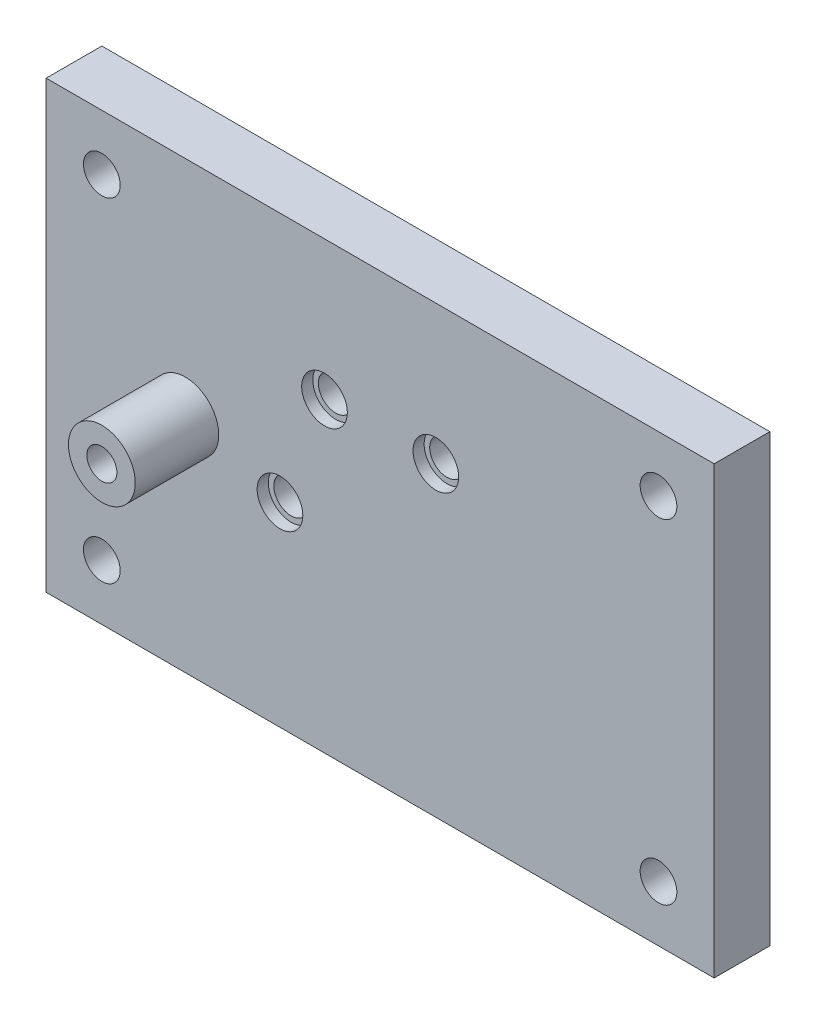
SolidWorks part; units mm, degrees
ref_plane "Front Plane" through (0, 0, 0) normal (0, 0, 1) x (1, 0, 0)
ref_plane "Top Plane" through (0, 0, 0) normal (0, 1, 0) x (1, 0, 0)
ref_plane "Right Plane" through (0, 0, 0) normal (1, 0, 0) x (0, 0, -1)
other "Configuration Table"
sketch "Sketch2" plane through (0, 0, 0) normal (0, 0, 1) x (1, 0, 0)
  line L1 (-60, -40) -> (60, -40)
  line L2 (-60, -40) -> (-60, 40)
  line L3 (-60, 40) -> (60, 40)
  line L4 (60, -40) -> (60, 40)
extrude "Base_plate" add sketch "Sketch2" along normal blind 10 from offset 0
sketch "Sketch3" plane through (0, 0, 0) normal (0, 0, 1) x (1, 0, 0)
  circle A0 centre (-35, 0) radius 6
extrude "Pivot_pedestal" add sketch "Sketch3" along normal blind 15 from offset 10
sketch "Sketch4" plane through (0, 0, 0) normal (0, 0, 1) x (1, 0, 0)
  circle A0 centre (-35, 0) radius 2.7
extrude "Pivot_clearance" cut sketch "Sketch4" along normal blind 25 from offset 0
sketch "Sketch5" plane through (0, 0, 0) normal (0, 0, 1) x (1, 0, 0)
  circle A0 centre (-10, 15) radius 3.1
extrude "Locator_clearance" cut sketch "Sketch5" along normal blind 10 from offset 0
sketch "Sketch6" plane through (0, 0, 0) normal (0, 0, 1) x (1, 0, 0)
  circle A0 centre (10, 15) radius 3.1
extrude "Cut-Extrude3" cut sketch "Sketch6" along normal blind 10 from offset 0
sketch "Sketch7" plane through (0, 0, 0) normal (0, 0, 1) x (1, 0, 0)
  circle A0 centre (-18, -5) radius 3.1
extrude "Side_locator_clearance" cut sketch "Sketch7" along normal blind 10 from offset 0
sketch "Sketch8" plane through (0, 0, 0) normal (0, 0, 1) x (1, 0, 0)
  circle A0 centre (-10, 15) radius 4.1
extrude "Locator_shoulder_counterbore" cut sketch "Sketch8" along normal blind 2 from offset 8
sketch "Sketch9" plane through (0, 0, 0) normal (0, 0, 1) x (1, 0, 0)
  circle A0 centre (10, 15) radius 4.1
extrude "Cut-Extrude6" cut sketch "Sketch9" along normal blind 2 from offset 8
sketch "Sketch10" plane through (0, 0, 0) normal (0, 0, 1) x (1, 0, 0)
  circle A0 centre (-18, -5) radius 4.1
extrude "Side_shoulder_counterbore" cut sketch "Sketch10" along normal blind 2 from offset 8
sketch "Sketch11" plane through (0, 0, 0) normal (0, 0, 1) x (1, 0, 0)
  circle A0 centre (-50, -30) radius 3.3
extrude "Bench_mount_M6_clearance" cut sketch "Sketch11" along normal blind 10 from offset 0
sketch "Sketch12" plane through (0, 0, 0) normal (0, 0, 1) x (1, 0, 0)
  circle A0 centre (-50, 30) radius 3.3
extrude "Cut-Extrude9" cut sketch "Sketch12" along normal blind 10 from offset 0
sketch "Sketch13" plane through (0, 0, 0) normal (0, 0, 1) x (1, 0, 0)
  circle A0 centre (50, -30) radius 3.3
extrude "Cut-Extrude10" cut sketch "Sketch13" along normal blind 10 from offset 0
sketch "Sketch14" plane through (0, 0, 0) normal (0, 0, 1) x (1, 0, 0)
  circle A0 centre (50, 30) radius 3.3
extrude "Cut-Extrude11" cut sketch "Sketch14" along normal blind 10 from offset 0
